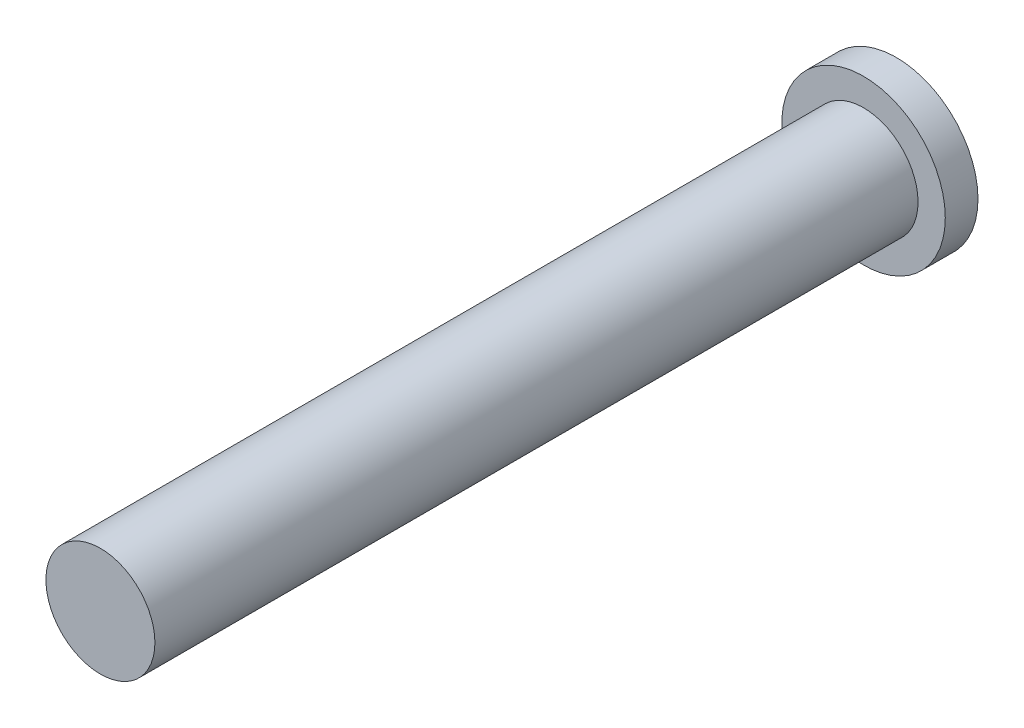
SolidWorks part; units mm, degrees
ref_plane "Front Plane" through (0, 0, 0) normal (0, 0, 1) x (1, 0, 0)
ref_plane "Top Plane" through (0, 0, 0) normal (0, 1, 0) x (1, 0, 0)
ref_plane "Right Plane" through (0, 0, 0) normal (1, 0, 0) x (0, 0, -1)
sketch "Sketch1" plane through (0, 0, 0) normal (0, 0, 1) x (1, 0, 0)
  circle A0 centre (0, 0) radius 7.5
  dimension "D1" = 15
extrude "Boss-Extrude1" add sketch "Sketch1" along normal blind 3
sketch "Sketch2" plane through (0, 0, 3) normal (0, 0, 1) x (1, 0, 0)
  circle A0 centre (0, 0) radius 5
  dimension "D1" = 10
extrude "Boss-Extrude2" add sketch "Sketch2" along normal blind 70
